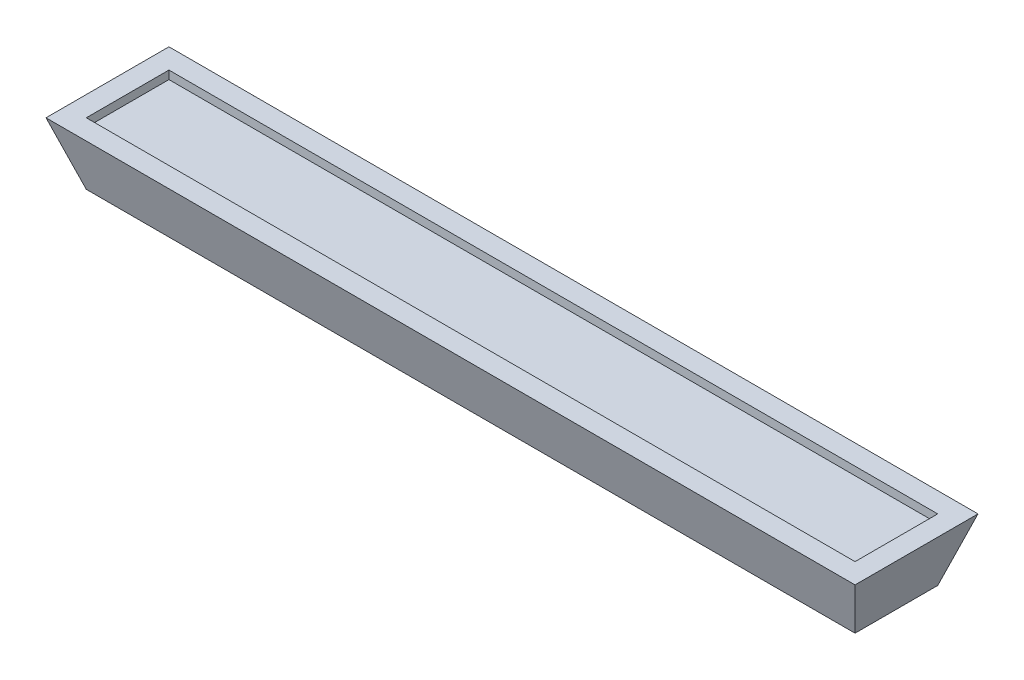
SolidWorks part; units mm, degrees
ref_plane "前视基准面" through (0, 0, 0) normal (0, 0, 1) x (1, 0, 0)
ref_plane "上视基准面" through (0, 0, 0) normal (0, 1, 0) x (1, 0, 0)
ref_plane "右视基准面" through (0, 0, 0) normal (1, 0, 0) x (0, 0, -1)
other "Configuration Table"
sketch "草图1" plane through (0, 0, 0) normal (0, 1, 0) x (1, 0, 0)
  line L1 (-93, 10) -> (93, 10)
  line L2 (-93, 10) -> (-93, -10)
  line L3 (-93, -10) -> (93, -10)
  line L4 (93, 10) -> (93, -10)
  line L5 (-93, 10) -> (93, -10) construction
  line L6 (-93, -10) -> (93, 10) construction
  point P0 (0, 0)
  dimension "D1" = 186
  dimension "D2" = 20
extrude "凸台-拉伸1" add sketch "草图1" along normal blind 15 draft 18 draft outward yes
sketch "草图2" plane through (0, 15, 0) normal (0, 1, 0) x (1, 0, 0)
  line L1 (-93, 10) -> (93, 10)
  line L2 (-93, 10) -> (-93, -10)
  line L3 (-93, -10) -> (93, -10)
  line L4 (93, 10) -> (93, -10)
  line L5 (-93, 10) -> (93, -10) construction
  line L6 (-93, -10) -> (93, 10) construction
  point P0 (0, 0)
  dimension "D1" = 186
  dimension "D2" = 20
extrude "切除-拉伸2" cut sketch "草图2" against normal blind 2
sketch "草图3" plane through (0, 0, 0) normal (0, -1, 0) x (1, 0, 0)
  line L1 (-88.5, 6.5) -> (88.5, 6.5)
  line L2 (-88.5, 6.5) -> (-88.5, -6.5)
  line L3 (-88.5, -6.5) -> (88.5, -6.5)
  line L4 (88.5, 6.5) -> (88.5, -6.5)
  line L5 (-88.5, 6.5) -> (88.5, -6.5) construction
  line L6 (-88.5, -6.5) -> (88.5, 6.5) construction
  point P0 (0, 0)
  dimension "D1" = 177
  dimension "D2" = 13
extrude "切除-拉伸3" cut sketch "草图3" against normal blind 4
sketch "草图4" plane through (0, 4, 0) normal (0, -1, 0) x (1, 0, 0)
  line L0 (0, 34.5012) -> (0, -30.2871) construction
  circle A0 centre (-72, 0) radius 2.75
  circle A1 centre (-38, 0) radius 2.75
  circle A2 centre (38, 0) radius 2.75
  circle A3 centre (72, 0) radius 2.75
  dimension "D5" = 5.5
  dimension "D6" = 5.5
  dimension "D7" = 5.5
  dimension "D8" = 5.5
  dimension "D1" = 38
  dimension "D2" = 72
  dimension "D3" = 38
  dimension "D4" = 72
extrude "切除-拉伸6" cut sketch "草图4" against normal blind 5.5
